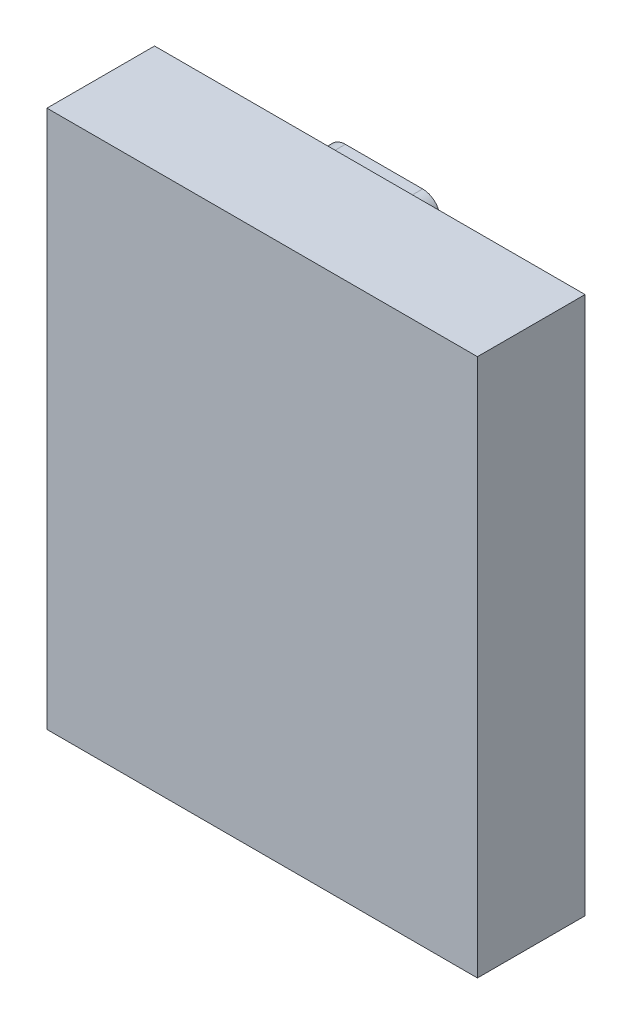
SolidWorks part; units mm, degrees
ref_plane "Front Plane" through (0, 0, 0) normal (0, 0, 1) x (1, 0, 0)
ref_plane "Top Plane" through (0, 0, 0) normal (0, 1, 0) x (1, 0, 0)
ref_plane "Right Plane" through (0, 0, 0) normal (1, 0, 0) x (0, 0, -1)
sketch "Sketch1" plane through (0, 0, 0) normal (0, 0, 1) x (1, 0, 0)
  line L1 (-65.3422, 55.7188) -> (14.6578, 55.7188)
  line L2 (-65.3422, 55.7188) -> (-65.3422, -44.2812)
  line L3 (-65.3422, -44.2812) -> (14.6578, -44.2812)
  line L4 (14.6578, 55.7188) -> (14.6578, -44.2812)
  dimension "D1" = 100
  dimension "D2" = 80
extrude "Boss-Extrude1" add sketch "Sketch1" along normal blind 20
sketch "Sketch2" plane through (0, 0, 0) normal (0, 0, -1) x (-1, 0, 0)
  line L1 (-6.9813, 46.1111) -> (57.0187, 46.1111)
  line L2 (-6.9813, 46.1111) -> (-6.9813, -33.8889)
  line L3 (-6.9813, -33.8889) -> (57.0187, -33.8889)
  line L4 (57.0187, 46.1111) -> (57.0187, -33.8889)
  dimension "D1" = 80
  dimension "D2" = 64
extrude "Cut-Extrude1" cut sketch "Sketch2" against normal blind 17 contours L4 L1 L2 L3
sketch "Sketch3" plane through (0, 0, 0) normal (0, 0, -1) x (-1, 0, 0)
  line L0 (18.5238, 51.3364) -> (32.8912, 51.3364) construction
  line L1 (18.5238, 54.6239) -> (32.8912, 54.6239)
  line L2 (18.5238, 48.049) -> (32.8912, 48.049)
  arc A0 (18.5238, 54.6239) -> (18.5238, 48.049) centre (18.5238, 51.3364) ccw
  arc A1 (32.8912, 48.049) -> (32.8912, 54.6239) centre (32.8912, 51.3364) ccw
  point P2 (25.7075, 51.3364)
extrude "Boss-Extrude2" add sketch "Sketch3" along normal blind 3
sketch "Sketch5" plane through (0, 0, 0) normal (0, 0, -1) x (-1, 0, 0)
  circle A0 centre (-0.8979, 51.1614) radius 3.1999
  point P2 (0, 0)
  point P3 (-3.914, 50.8598)
extrude "Cut-Extrude2" cut sketch "Sketch5" against normal blind 2.7
ref_plane "Plane1" through (-65.3422, 55.7188, 0) normal (0, -1, 0) x (-1, 0, 0)
sketch "Sketch8" plane through (0, -44.2812, 0) normal (0, -1, 0) x (1, 0, 0)
  line L0 (-58.0956, 9.9271) -> (-49.7757, 9.9271) construction
  line L1 (-58.0956, 11.5344) -> (-49.7757, 11.5344)
  line L2 (-58.0956, 8.3199) -> (-49.7757, 8.3199)
  arc A0 (-58.0956, 11.5344) -> (-58.0956, 8.3199) centre (-58.0956, 9.9271) ccw
  arc A1 (-49.7757, 8.3199) -> (-49.7757, 11.5344) centre (-49.7757, 9.9271) ccw
  point P2 (-53.9357, 9.9271)
extrude "Cut-Extrude3" cut sketch "Sketch8" against normal blind 5
